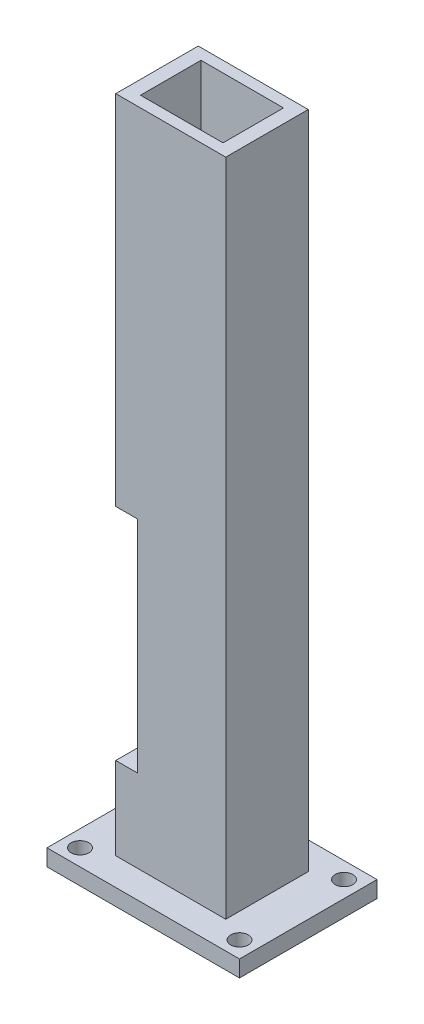
SolidWorks part; units mm, degrees
ref_plane "前视基准面" through (0, 0, 0) normal (0, 0, 1) x (1, 0, 0)
ref_plane "上视基准面" through (0, 0, 0) normal (0, 1, 0) x (1, 0, 0)
ref_plane "右视基准面" through (0, 0, 0) normal (1, 0, 0) x (0, 0, -1)
sketch "草图1" plane through (0, 0, 0) normal (0, 1, 0) x (1, 0, 0)
  line L1 (-17.5, -12.5) -> (17.5, -12.5)
  line L2 (-17.5, -12.5) -> (-17.5, 12.5)
  line L3 (-17.5, 12.5) -> (17.5, 12.5)
  line L4 (17.5, -12.5) -> (17.5, 12.5)
  line L5 (-17.5, -12.5) -> (17.5, 12.5) construction
  line L6 (-17.5, 12.5) -> (17.5, -12.5) construction
  point P0 (0, 0)
  dimension "D1" = 35
  dimension "D2" = 25
extrude "凸台-拉伸1" add sketch "草图1" along normal blind 3
sketch "草图2" plane through (0, 3, 0) normal (0, 1, 0) x (1, 0, 0)
  line L1 (-10, -7.5) -> (10, -7.5)
  line L2 (-10, -7.5) -> (-10, 7.5)
  line L3 (-10, 7.5) -> (10, 7.5)
  line L4 (10, -7.5) -> (10, 7.5)
  line L5 (-10, -7.5) -> (10, 7.5) construction
  line L6 (-10, 7.5) -> (10, -7.5) construction
  point P0 (0, 0)
  dimension "D1" = 20
  dimension "D2" = 15
extrude "凸台-拉伸2" add sketch "草图2" along normal blind 120
sketch "草图3" plane through (0, 123, 0) normal (0, 1, 0) x (1, 0, 0)
  line L1 (-7.5, -5.5) -> (7.5, -5.5)
  line L2 (-7.5, -5.5) -> (-7.5, 5.5)
  line L3 (-7.5, 5.5) -> (7.5, 5.5)
  line L4 (7.5, -5.5) -> (7.5, 5.5)
  line L5 (-7.5, -5.5) -> (7.5, 5.5) construction
  line L6 (-7.5, 5.5) -> (7.5, -5.5) construction
  point P0 (0, 0)
  dimension "D1" = 11
  dimension "D2" = 15
extrude "切除-拉伸1" cut sketch "草图3" against normal up to next
sketch "草图4" plane through (0, 0, 7.5) normal (0, 0, 1) x (1, 0, 0)
  line L0 (-10, 58) -> (-6, 58)
  line L1 (-10, 123) -> (-10, 3) construction
  line L2 (-6, 58) -> (-6, 18)
  line L3 (-6, 18) -> (-10, 18)
  line L5 (-17.5, 3) -> (17.5, 3) construction
  line L6 (-10, 58) -> (-10, 18)
  dimension "D1" = 40
  dimension "D2" = 15
  dimension "D3" = 4
extrude "切除-拉伸2" cut sketch "草图4" against normal up to next
sketch "草图5" plane through (0, 3, 0) normal (0, 1, 0) x (1, 0, 0)
  line L0 (0, 12.5) -> (0, -12.5) construction
  line L1 (17.5, 12.5) -> (-17.5, 12.5) construction
  line L2 (-17.5, -12.5) -> (17.5, -12.5) construction
  line L3 (-17.5, 0) -> (17.5, 0) construction
  line L4 (-17.5, 12.5) -> (-17.5, -12.5) construction
  line L5 (17.5, -12.5) -> (17.5, 12.5) construction
  circle A0 centre (-14.5, 9.5) radius 1.6
  circle A1 centre (14.5, 9.5) radius 1.6
  circle A2 centre (-14.5, -9.5) radius 1.6
  circle A3 centre (14.5, -9.5) radius 1.6
  dimension "D1" = 3.2
  dimension "D2" = 3.2
  dimension "D3" = 3.2
  dimension "D4" = 3.2
  dimension "D5" = 3
  dimension "D6" = 3
  dimension "D7" = 3
  dimension "D8" = 3
  dimension "D9" = 3
  dimension "D10" = 3
  dimension "D11" = 3
  dimension "D12" = 3
extrude "切除-拉伸3" cut sketch "草图5" against normal up to next
